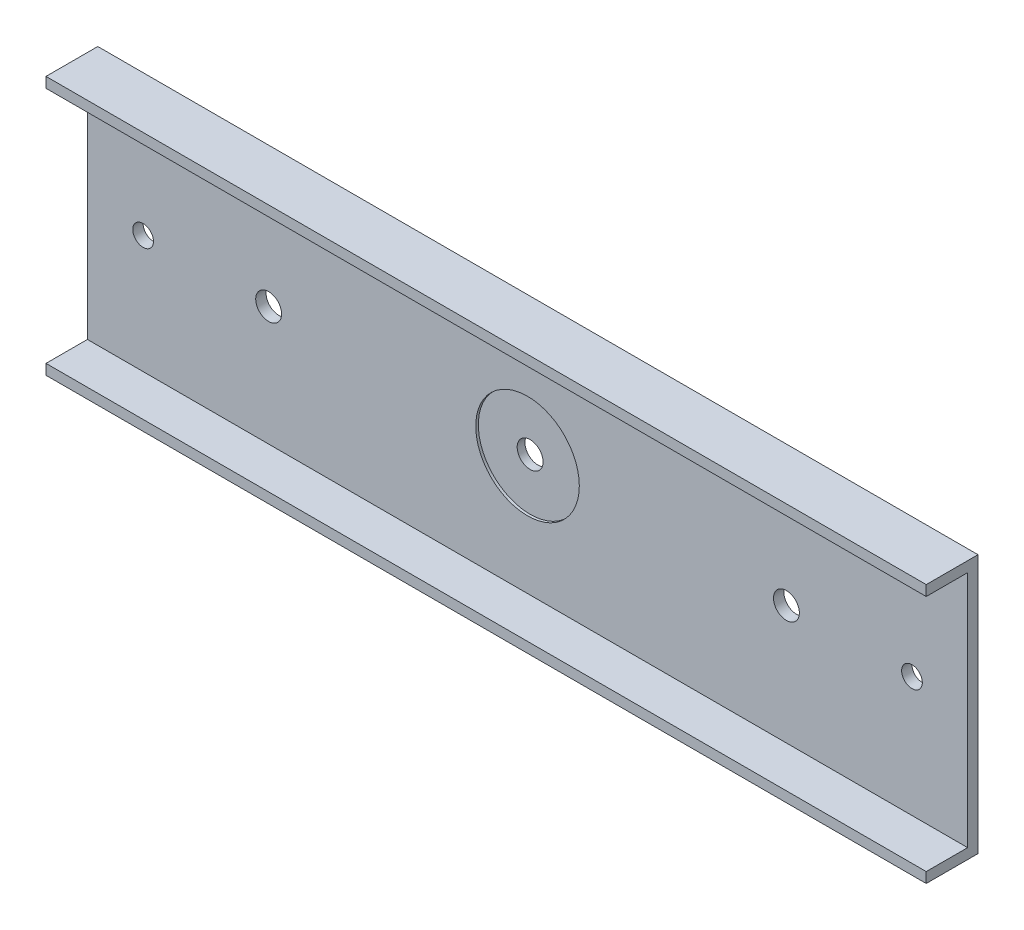
SolidWorks part; units mm, degrees
ref_plane "Front Plane" through (0, 0, 0) normal (0, 0, 1) x (1, 0, 0)
ref_plane "Top Plane" through (0, 0, 0) normal (0, 1, 0) x (1, 0, 0)
ref_plane "Right Plane" through (0, 0, 0) normal (1, 0, 0) x (0, 0, -1)
sketch "Sketch1" plane through (0, 0, 0) normal (0, 0, 1) x (1, 0, 0)
  line L1 (-85, -25) -> (85, -25)
  line L2 (-85, -25) -> (-85, 25)
  line L3 (-85, 25) -> (85, 25)
  line L4 (85, -25) -> (85, 25)
  line L5 (-85, -25) -> (85, 25) construction
  line L6 (-85, 25) -> (85, -25) construction
  point P0 (0, 0)
  dimension "D1" = 170
  dimension "D2" = 50
extrude "Boss-Extrude1" add sketch "Sketch1" along normal blind 2
sketch "Sketch2" plane through (0, 25, 0) normal (0, 1, 0) x (1, 0, 0)
  line L1 (-85, 0) -> (85, 0)
  line L2 (-85, 0) -> (-85, -10)
  line L3 (-85, -10) -> (85, -10)
  line L4 (85, 0) -> (85, -10)
  dimension "D1" = 170
  dimension "D2" = 10
extrude "Boss-Extrude2" add sketch "Sketch2" against normal blind 2
sketch "Sketch3" plane through (0, -25, 0) normal (0, -1, 0) x (1, 0, 0)
  line L1 (-85, 0) -> (85, 0)
  line L2 (-85, 0) -> (-85, 10)
  line L3 (-85, 10) -> (85, 10)
  line L4 (85, 0) -> (85, 10)
extrude "Boss-Extrude3" add sketch "Sketch3" against normal blind 2
sketch "Sketch4" plane through (0, 0, 0) normal (0, 0, -1) x (-1, 0, 0)
  circle A1 centre (0, 0) radius 2.5
  circle A6 centre (-50, 0) radius 2.5
  circle A7 centre (50, 0) radius 2.5
  dimension "D1" = 5
  dimension "D2" = 5
  dimension "D3" = 5
  dimension "D4" = 50
  dimension "D5" = 50
extrude "Cut-Extrude1" cut sketch "Sketch4" against normal blind 2
sketch "Sketch5" plane through (0, 0, 2) normal (0, 0, 1) x (1, 0, 0)
  circle A0 centre (0, 0) radius 10
  dimension "D1" = 20
extrude "Cut-Extrude2" cut sketch "Sketch5" against normal blind 0.5
sketch "Sketch7" plane through (0, 0, 0) normal (0, 0, -1) x (-1, 0, 0)
  line L0 (-85, 25) -> (85, 25) construction
  line L1 (85, 25) -> (85, -25) construction
  line L2 (-85, -25) -> (-85, 25) construction
  circle A0 centre (-74.2459, 0.2257) radius 2
  circle A1 centre (74.2459, -0.2257) radius 2
  dimension "D2" = 4
  dimension "D6" = 4
  dimension "D1" = 25.2257
  dimension "D3" = 10.7541
  dimension "D4" = 10.7541
  dimension "D5" = 24.7743
extrude "Cut-Extrude4" cut sketch "Sketch7" against normal blind 30
